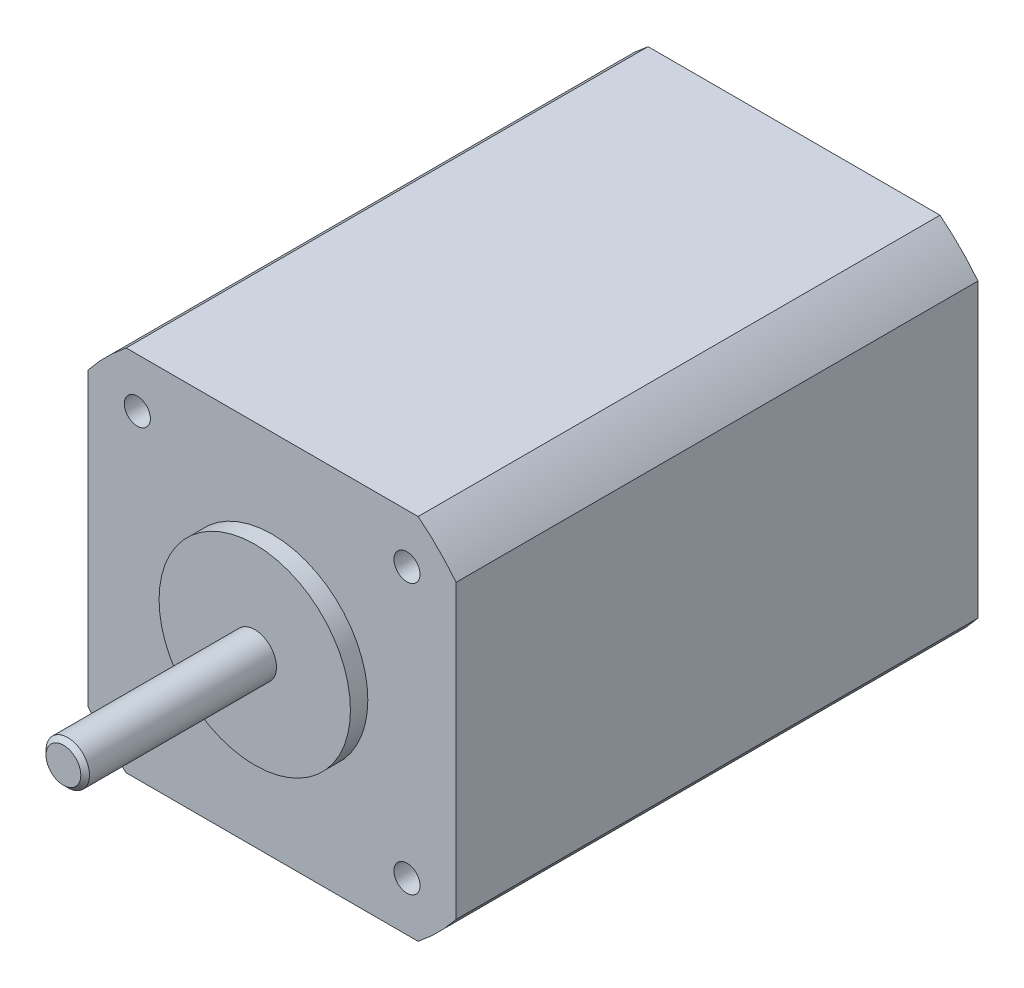
SolidWorks part; units mm, degrees
ref_plane "Front Plane" through (0, 0, 0) normal (0, 0, 1) x (1, 0, 0)
ref_plane "Top Plane" through (0, 0, 0) normal (0, 1, 0) x (1, 0, 0)
ref_plane "Right Plane" through (0, 0, 0) normal (1, 0, 0) x (0, 0, -1)
sketch "Sketch1" plane through (0, 0, 0) normal (0, 0, 1) x (1, 0, 0)
  line L1 (-21.15, -21.15) -> (21.15, -21.15)
  line L2 (-21.15, -21.15) -> (-21.15, 21.15)
  line L3 (-21.15, 21.15) -> (21.15, 21.15)
  line L4 (21.15, -21.15) -> (21.15, 21.15)
  line L5 (-21.15, -21.15) -> (21.15, 21.15) construction
  line L6 (-21.15, 21.15) -> (21.15, -21.15) construction
  point P0 (0, 0)
  dimension "D1" = 42.3
  dimension "D2" = 42.3
extrude "Boss-Extrude1" add sketch "Sketch1" along normal blind 60
sketch "Sketch2" plane through (0, 0, 60) normal (0, 0, 1) x (1, 0, 0)
  line L1 (-15.5, -15.5) -> (15.5, -15.5) construction
  line L2 (-15.5, -15.5) -> (-15.5, 15.5) construction
  line L3 (-15.5, 15.5) -> (15.5, 15.5) construction
  line L4 (15.5, -15.5) -> (15.5, 15.5) construction
  line L5 (-15.5, -15.5) -> (15.5, 15.5) construction
  line L6 (-15.5, 15.5) -> (15.5, -15.5) construction
  circle A0 centre (-15.5, 15.5) radius 1.5
  circle A1 centre (-15.5, -15.5) radius 1.5
  circle A2 centre (15.5, -15.5) radius 1.5
  circle A3 centre (15.5, 15.5) radius 1.5
  point P0 (0, 0)
  dimension "D2" = 3
  dimension "D1" = 31
extrude "Cut-Extrude1" cut sketch "Sketch2" against normal blind 4.5
sketch "Sketch3" plane through (0, 0, 60) normal (0, 0, 1) x (1, 0, 0)
  line L1 (35.04, -31.0506) -> (-35.04, -31.0506)
  line L2 (35.04, -31.0506) -> (35.04, 31.0506)
  line L3 (35.04, 31.0506) -> (-35.04, 31.0506)
  line L4 (-35.04, -31.0506) -> (-35.04, 31.0506)
  line L5 (35.04, -31.0506) -> (-35.04, 31.0506) construction
  line L6 (35.04, 31.0506) -> (-35.04, -31.0506) construction
  circle A0 centre (0, 0) radius 27
  dimension "D1" = 54
extrude "Cut-Extrude2" cut sketch "Sketch3" against normal through all
sketch "Sketch4" plane through (0, 0, 60) normal (0, 0, 1) x (1, 0, 0)
  circle A0 centre (0, 0) radius 11
  dimension "D1" = 22
extrude "Boss-Extrude2" add sketch "Sketch4" along normal blind 2
sketch "Sketch5" plane through (0, 0, 60) normal (0, 0, 1) x (1, 0, 0)
  circle A0 centre (0, 0) radius 2.5
  dimension "D1" = 5
extrude "Boss-Extrude3" add sketch "Sketch5" along normal blind 24
chamfer "Chamfer1" distance 0.5 angle 45 1 edges at (2.5, 0, 84)
